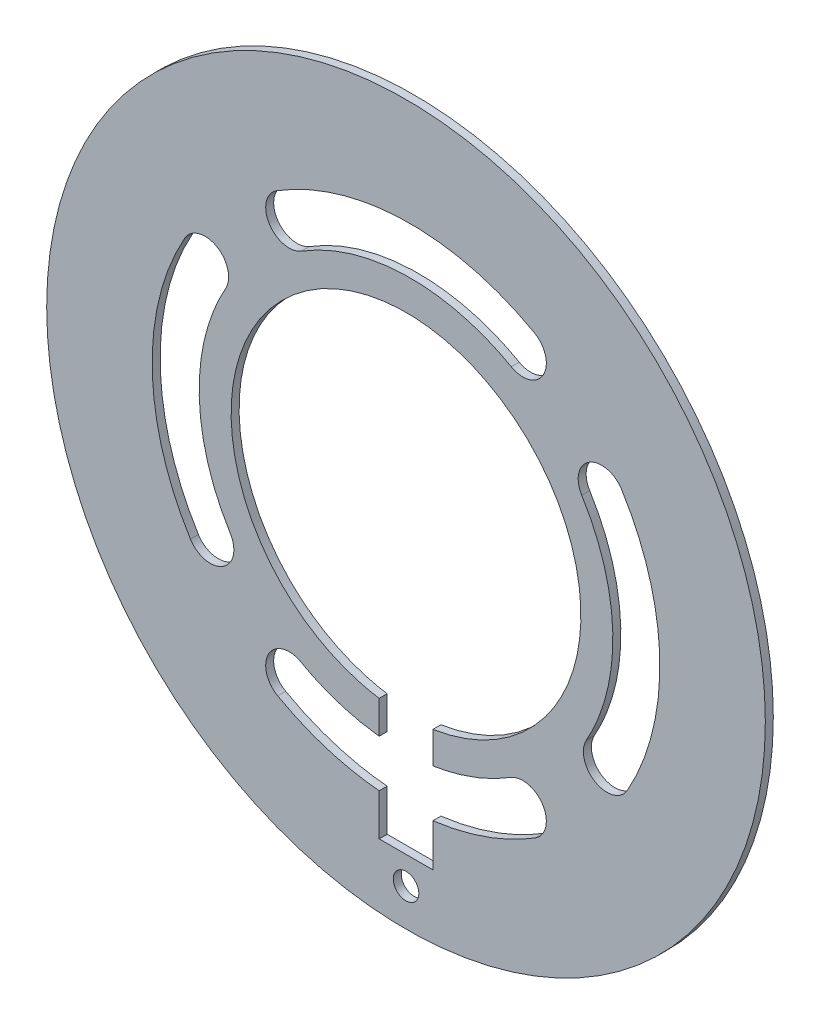
SolidWorks part; units mm, degrees
ref_plane "Front Plane" through (0, 0, 0) normal (0, 0, 1) x (1, 0, 0)
ref_plane "Top Plane" through (0, 0, 0) normal (0, 1, 0) x (1, 0, 0)
ref_plane "Right Plane" through (0, 0, 0) normal (1, 0, 0) x (0, 0, -1)
sketch "Model" plane through (0, 0, 0) normal (0, 0, 1) x (1, 0, 0)
  line L0 (588.2631, 439.4907) -> (588.2631, 432.4678)
  line L1 (609.6264, 432.4678) -> (609.6264, 439.8691)
  line L2 (609.6264, 458.7367) -> (609.6264, 471.3262)
  line L3 (588.2631, 471.3221) -> (588.2631, 458.2704)
  line L4 (588.2631, 432.4678) -> (588.2631, 422.9428)
  line L5 (609.6264, 432.4678) -> (609.6264, 422.9428)
  line L6 (588.2631, 422.9428) -> (609.6264, 422.9428)
  circle A0 centre (598.9315, 540.0287) radius 142.875
  circle A1 centre (598.9447, 411.9954) radius 5.08
  spline S0 degree 3 poles (670.6698, 498.1643) (668.1395, 493.6664) (669.7345, 487.9689) (678.7303, 482.9083) (684.4278, 484.5033) (686.9581, 489.0012) knots 0 0 0 0 1 1 2 2 2 2
  spline S1 degree 3 poles (686.9581, 489.0012) (704.9573, 520.9964) (704.0774, 560.2604) (684.6631, 591.4172) knots 0 0 0 0 1 1 1 1
  spline S2 degree 3 poles (684.6631, 591.4172) (681.9338, 595.7973) (676.1706, 597.1355) (667.4105, 591.6769) (666.0723, 585.9137) (668.8016, 581.5337) knots 0 0 0 0 1 1 2 2 2 2
  spline S3 degree 3 poles (670.6698, 498.1643) (685.3216, 524.2093) (684.6054, 556.1712) (668.8016, 581.5337) knots 0 0 0 0 1 1 1 1
  spline S4 degree 3 poles (640.7963, 611.7671) (645.2942, 609.2368) (650.9917, 610.8318) (656.0523, 619.8276) (654.4573, 625.5251) (649.9594, 628.0554) knots 0 0 0 0 1 1 2 2 2 2
  spline S5 degree 3 poles (649.9594, 628.0554) (617.9642, 646.0546) (578.7002, 645.1747) (547.5434, 625.7604) knots 0 0 0 0 1 1 1 1
  spline S6 degree 3 poles (547.5434, 625.7604) (543.1634, 623.0311) (541.8252, 617.2679) (547.2837, 608.5078) (553.0469, 607.1696) (557.4269, 609.8989) knots 0 0 0 0 1 1 2 2 2 2
  spline S7 degree 3 poles (640.7963, 611.7671) (614.7514, 626.4189) (582.7894, 625.7027) (557.4269, 609.8989) knots 0 0 0 0 1 1 1 1
  spline S8 degree 3 poles (557.067, 468.2908) (566.6835, 462.881) (577.295, 459.4725) (588.2631, 458.2704) knots 0 0 0 0 1 1 1 1
  spline S9 degree 3 poles (557.067, 468.2908) (552.5691, 470.8211) (546.8716, 469.2261) (541.811, 460.2303) (543.406, 454.5328) (547.9039, 452.0025) knots 0 0 0 0 1 1 2 2 2 2
  spline S10 degree 3 poles (547.9039, 452.0025) (560.3182, 445.0187) (574.0753, 440.7539) (588.2631, 439.4907) knots 0 0 0 0 1 1 1 1
  spline S11 degree 3 poles (609.6264, 439.8691) (624.0761, 441.6734) (637.961, 446.5965) (650.3199, 454.2975) knots 0 0 0 0 1 1 1 1
  spline S12 degree 3 poles (650.3199, 454.2975) (654.7, 457.0268) (656.0382, 462.79) (650.5796, 471.5501) (644.8164, 472.8883) (640.4364, 470.159) knots 0 0 0 0 1 1 2 2 2 2
  spline S13 degree 3 poles (609.6264, 458.7367) (620.5633, 460.4211) (631.0447, 464.3069) (640.4364, 470.159) knots 0 0 0 0 1 1 1 1
  spline S14 degree 3 poles (609.6264, 471.3262) (647.5698, 477.2328) (673.5407, 512.7803) (661.7275, 588.667) (626.18, 614.6379) (550.2933, 602.8247) (524.3224, 567.2772) (530.229, 529.3339) (534.8847, 499.4261) (558.3535, 475.9663) (588.2631, 471.3221) knots 0 0 0 0 1 1 2 2 3 3 3 4 4 4 4
  spline S15 degree 3 poles (527.1935, 581.8936) (529.7238, 586.3915) (528.1288, 592.089) (519.133, 597.1497) (513.4355, 595.5546) (510.9052, 591.0567) knots 0 0 0 0 1 1 2 2 2 2
  spline S16 degree 3 poles (510.9052, 591.0567) (492.906, 559.0615) (493.7859, 519.7975) (513.2002, 488.6407) knots 0 0 0 0 1 1 1 1
  spline S17 degree 3 poles (513.2002, 488.6407) (515.9295, 484.2607) (521.6927, 482.9225) (530.4528, 488.381) (531.791, 494.1442) (529.0617, 498.5242) knots 0 0 0 0 1 1 2 2 2 2
  spline S18 degree 3 poles (527.1935, 581.8936) (512.5417, 555.8487) (513.2579, 523.8867) (529.0617, 498.5242) knots 0 0 0 0 1 1 1 1
extrude "Boss-Extrude1" add sketch "Model" along normal blind 3.175
